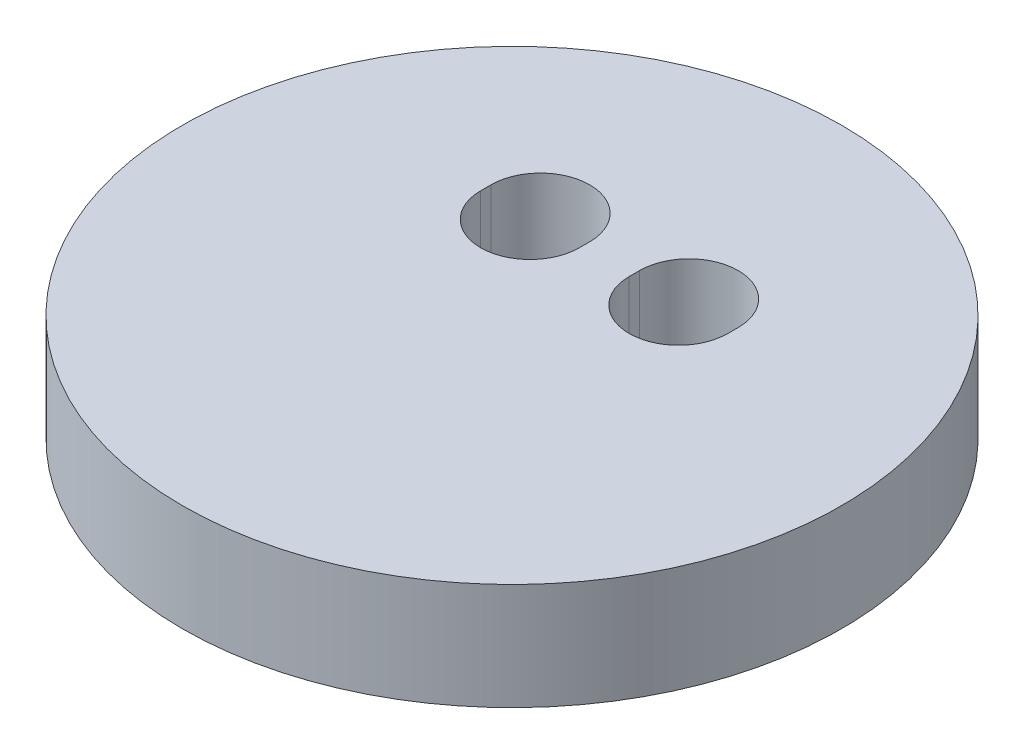
SolidWorks part; units mm, degrees
ref_plane "Front Plane" through (0, 0, 0) normal (0, 0, 1) x (1, 0, 0)
ref_plane "Top Plane" through (0, 0, 0) normal (0, 1, 0) x (1, 0, 0)
ref_plane "Right Plane" through (0, 0, 0) normal (1, 0, 0) x (0, 0, -1)
sketch "Sketch1" plane through (0, 0, 0) normal (0, 1, 0) x (1, 0, 0)
  circle A0 centre (0, 0) radius 12.36
  point P3 (0, 0)
  dimension "D1" = 24.72
extrude "Boss-Extrude1" add sketch "Sketch1" along normal blind 4
sketch "Sketch2" plane through (0, 4, 0) normal (0, 1, 0) x (1, 0, 0)
  line L0 (-2.785, 3.85) -> (-2.785, 3.46) construction
  line L1 (2.785, 3.85) -> (2.785, 3.46) construction
  line L2 (4.635, 3.85) -> (4.635, 3.46)
  line L3 (0.935, 3.85) -> (0.935, 3.46)
  line L4 (-0.935, 3.85) -> (-0.935, 3.46)
  line L5 (-4.635, 3.85) -> (-4.635, 3.46)
  line L6 (-2.785, 5.7) -> (2.785, 5.7) construction
  arc A3 (4.635, 3.85) -> (0.935, 3.85) centre (2.785, 3.85) ccw
  arc A4 (0.935, 3.46) -> (4.635, 3.46) centre (2.785, 3.46) ccw
  arc A5 (-0.935, 3.85) -> (-4.635, 3.85) centre (-2.785, 3.85) ccw
  arc A6 (-4.635, 3.46) -> (-0.935, 3.46) centre (-2.785, 3.46) ccw
  circle A7 centre (0, 0) radius 12.36 construction
  point P1 (-2.785, 3.655)
  point P2 (-4.635, 3.655)
  point P3 (-0.935, 3.655)
  point P8 (2.785, 3.655)
  point P14 (2.785, 5.7)
  point P15 (2.785, 1.61)
  point P16 (4.635, 3.655)
  point P17 (0.935, 3.655)
  point P20 (-2.785, 5.7)
  point P24 (-2.785, 1.61)
  point P29 (0, 5.7)
  dimension "D2" = 4.09
  dimension "D1" = 3.7
  dimension "D3" = 3.7
  dimension "D4" = 4.09
  dimension "D5" = 5.7
  dimension "D6" = 5.57
extrude "Cut-Extrude1" cut sketch "Sketch2" against normal through all
